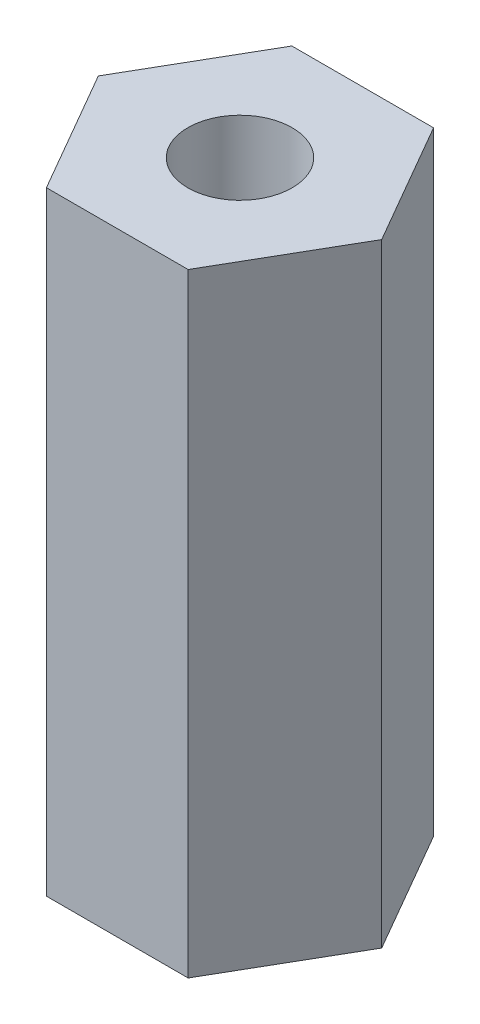
SolidWorks part; units mm, degrees
ref_plane "Alzado" through (0, 0, 0) normal (0, 0, 1) x (1, 0, 0)
ref_plane "Planta" through (0, 0, 0) normal (0, 1, 0) x (1, 0, 0)
ref_plane "Vista lateral" through (0, 0, 0) normal (1, 0, 0) x (0, 0, -1)
sketch "Croquis1" plane through (0, 0, 0) normal (0, 1, 0) x (1, 0, 0)
  line L1 (4.6188, 0) -> (2.3094, 4)
  line L2 (2.3094, 4) -> (-2.3094, 4)
  line L3 (-2.3094, 4) -> (-4.6188, 0)
  line L4 (-4.6188, 0) -> (-2.3094, -4)
  line L5 (-2.3094, -4) -> (2.3094, -4)
  line L6 (2.3094, -4) -> (4.6188, 0)
  circle A0 centre (0, 0) radius 1.7
  circle A1 centre (0, 0) radius 4 construction
  dimension "D1" = 3.4
  dimension "D2" = 8
extrude "Saliente-Extruir1" add sketch "Croquis1" along normal mid plane 20 contours L5 L6 L1 L2 L3 L4 A0
